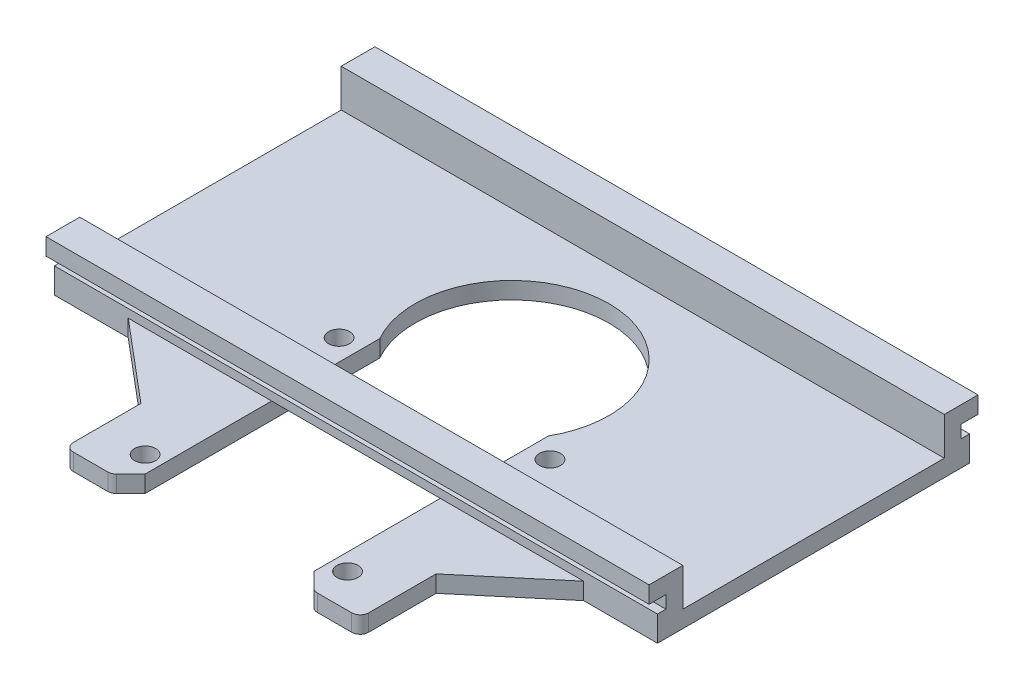
SolidWorks part; units mm, degrees
material "ABS"
ref_plane "Alzado" through (0, 0, 0) normal (0, 0, 1) x (1, 0, 0)
ref_plane "Planta" through (0, 0, 0) normal (0, 1, 0) x (1, 0, 0)
ref_plane "Vista lateral" through (0, 0, 0) normal (1, 0, 0) x (0, 0, -1)
sketch "Croquis1" plane through (0, 0, 0) normal (0, 1, 0) x (1, 0, 0)
  line L18 (36.2248, -45.2797) -> (34.5176, -43.5726)
  line L19 (34.5176, -15.7515) -> (34.5176, -43.5726)
  line L22 (42.0176, -44.5726) -> (42.0176, -36.5726)
  line L23 (41.0176, -45.5726) -> (36.9319, -45.5726)
  line L26 (60.2676, 8.4274) -> (-11.2324, 8.4274)
  line L27 (60.2676, 8.4274) -> (60.2676, -28.5726)
  line L30 (60.2676, -28.5726) -> (51.5176, -28.5726)
  line L34 (-11.2324, -28.5726) -> (-2.4824, -28.5726)
  line L35 (-11.2324, 8.4274) -> (-11.2324, -28.5726)
  line L36 (8.0176, -45.5726) -> (12.1034, -45.5726)
  line L37 (7.0176, -44.5726) -> (7.0176, -36.5726)
  line L38 (14.5176, -15.7515) -> (14.5176, -43.5726)
  line L39 (12.8105, -45.2797) -> (14.5176, -43.5726)
  line L42 (-2.4824, -28.5726) -> (7.0176, -36.5726)
  line L43 (42.0176, -36.5726) -> (51.5176, -28.5726)
  arc A0 (34.5176, -15.7515) -> (14.5176, -15.7515) centre (24.5176, -10.0726) ccw
  circle A7 centre (37.0176, -18.0726) radius 1.25
  circle A8 centre (36.5176, -41.5726) radius 1.25
  arc A9 (41.0176, -45.5726) -> (42.0176, -44.5726) centre (41.0176, -44.5726) ccw
  arc A10 (36.2248, -45.2797) -> (36.9319, -45.5726) centre (36.9319, -44.5726) ccw
  arc A11 (12.8105, -45.2797) -> (12.1034, -45.5726) centre (12.1034, -44.5726) cw
  arc A12 (8.0176, -45.5726) -> (7.0176, -44.5726) centre (8.0176, -44.5726) cw
  circle A13 centre (12.5176, -41.5726) radius 1.25
  circle A14 centre (12.0176, -18.0726) radius 1.25
  point P33 (14.5176, -45.5726)
  point P34 (12.5176, -45.5726)
  point P36 (7.0176, -45.5726)
  point P41 (42.0176, -45.5726)
  point P42 (36.5176, -45.5726)
  point P43 (34.5176, -45.5726)
  dimension "D2" = 54
  dimension "D8" = 37
  dimension "D3" = 37
  dimension "D10" = 54
  dimension "D11" = 8.75
extrude "Saliente-Extruir1" add sketch "Croquis1" against normal blind 2
sketch "Croquis3" plane through (60.2676, 0, 0) normal (1, 0, 0) x (0, 0, -1)
  line L0 (-25.5726, 0) -> (-25.5726, 4.5)
  line L9 (-28.5726, 0) -> (-25.5726, 0)
  line L10 (-28.5726, 1) -> (-28.5726, 0)
  line L11 (-27.5726, 1) -> (-28.5726, 1)
  line L12 (-27.5726, 2.5) -> (-27.5726, 1)
  line L13 (-29.5726, 2.5) -> (-27.5726, 2.5)
  line L14 (-29.5726, 4.5) -> (-29.5726, 2.5)
  line L15 (-25.5726, 4.5) -> (-29.5726, 4.5)
  line L17 (5.4274, 4.5) -> (9.4274, 4.5)
  line L18 (9.4274, 4.5) -> (9.4274, 2.5)
  line L19 (9.4274, 2.5) -> (7.4274, 2.5)
  line L20 (7.4274, 2.5) -> (7.4274, 1)
  line L21 (7.4274, 1) -> (8.4274, 1)
  line L22 (8.4274, 1) -> (8.4274, 0)
  line L23 (8.4274, 0) -> (5.4274, 0)
  line L24 (5.4274, 0) -> (5.4274, 4.5)
  dimension "D1" = 4.5
  dimension "D2" = 4
  dimension "D3" = 2
  dimension "D4" = 2
  dimension "D5" = 1.5
  dimension "D6" = 1
extrude "Saliente-Extruir2" add sketch "Croquis3" against normal blind 71.5
